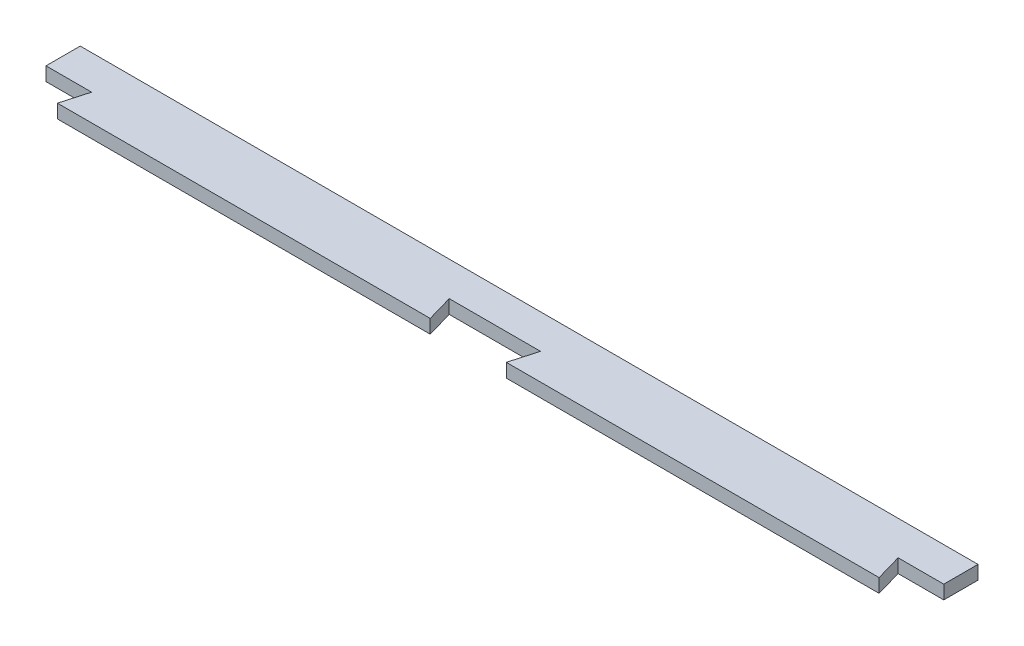
SolidWorks part; units mm, degrees
ref_plane "Front Plane" through (0, 0, 0) normal (0, 0, 1) x (1, 0, 0)
ref_plane "Top Plane" through (0, 0, 0) normal (0, 1, 0) x (1, 0, 0)
ref_plane "Right Plane" through (0, 0, 0) normal (1, 0, 0) x (0, 0, -1)
sketch "Sketch1" plane through (0, 0, 0) normal (0, 1, 0) x (1, 0, 0)
  line L0 (0, 17.5) -> (30, 17.5)
  line L1 (0, 0) -> (590, 0)
  line L2 (0, 0) -> (0, 35)
  line L3 (0, 35) -> (590, 35)
  line L4 (590, 0) -> (590, 35)
  line L5 (30, 17.5) -> (25, 0)
  line L6 (295, 35) -> (295, 0) construction
  line L7 (325, 17.5) -> (265, 17.5)
  line L8 (265, 17.5) -> (270, 0)
  line L9 (325, 17.5) -> (320, 0)
  line L10 (560, 17.5) -> (565, 0)
  line L11 (590, 17.5) -> (560, 17.5)
  line L13 (0, 35) -> (590, 35)
  line L14 (0, 35) -> (0, 40)
  line L15 (0, 40) -> (590, 40)
  line L16 (590, 35) -> (590, 40)
  point P15 (295, 17.5)
  dimension "D1" = 590
  dimension "D2" = 35
  dimension "D3" = 30
  dimension "D4" = 25
  dimension "D5" = 30
  dimension "D6" = 25
  dimension "D7" = 5
extrude "Boss-Extrude1" add sketch "Sketch1" along normal blind 9 contours L6 L3 L2 L0 L5 L1 L8 L7 | L3 L6 L7 L9 L1 L10 L11 L4 | L3 L13 L16 L15 L14
